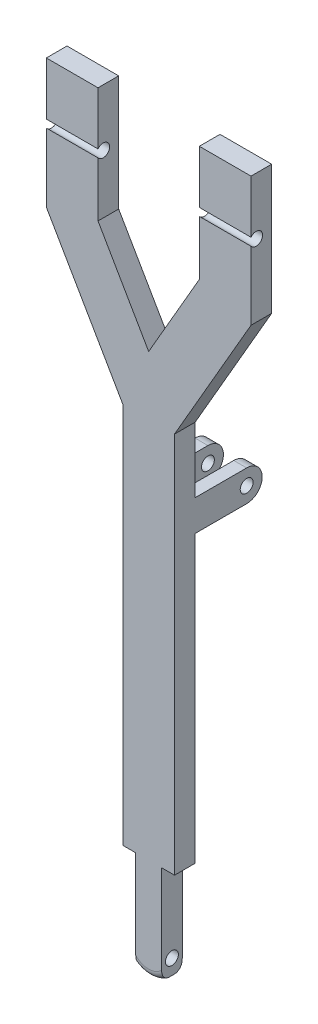
SolidWorks part; units mm, degrees
ref_plane "Plan de face" through (0, 0, 0) normal (0, 0, 1) x (1, 0, 0)
ref_plane "Plan de dessus" through (0, 0, 0) normal (0, 1, 0) x (1, 0, 0)
ref_plane "Plan de droite" through (0, 0, 0) normal (1, 0, 0) x (0, 0, -1)
sketch "Esquisse1" plane through (0, 0, 0) normal (0, 0, 1) x (1, 0, 0)
  line L0 (0, 0) -> (0, -900) construction
  line L1 (0, 0) -> (202.0726, 350) construction
  line L2 (0, 0) -> (-202.0726, 350) construction
  line L3 (0, -900) -> (0, 0) construction
  line L4 (-50, -900) -> (-50, 0)
  line L5 (50, -900) -> (50, 0)
  line L6 (0, 0) -> (202.0726, 350) construction
  line L8 (43.3013, -25) -> (198.0188, 242.9786)
  line L9 (-202.0726, 350) -> (0, 0) construction
  line L10 (-98.0188, 269.7735) -> (0, 100)
  line L11 (-198.0188, 242.9786) -> (-43.3013, -25)
  line L14 (-198.0188, 242.9786) -> (-198.0188, 492.9786)
  line L15 (-198.0188, 492.9786) -> (198.0188, 492.9786)
  line L16 (198.0188, 242.9786) -> (198.0188, 492.9786)
  line L20 (-98.0188, 342.9786) -> (-98.0188, 392.9786)
  line L22 (98.0188, 342.9786) -> (98.0188, 392.9786)
  line L24 (-98.0188, 342.9786) -> (-98.0188, 269.7735)
  line L26 (98.0188, 269.7735) -> (98.0188, 342.9786)
  line L27 (98.0188, 492.9786) -> (-98.0188, 492.9786)
  line L28 (-98.0188, 392.9786) -> (98.0188, 392.9786) construction
  line L29 (-98.0188, 342.9786) -> (98.0188, 342.9786) construction
  line L30 (-98.0188, 492.9786) -> (-98.0188, 392.9786)
  line L31 (98.0188, 392.9786) -> (98.0188, 492.9786)
  line L32 (0, 100) -> (98.0188, 269.7735)
  line L33 (-198.0188, 242.9786) -> (198.0188, 242.9786) construction
  arc A0 (-50, -900) -> (50, -900) centre (0, -900) ccw
  arc A1 (50, 0) -> (-50, 0) centre (0, 0) ccw
  arc A2 (-43.3013, 25) -> (-50, 0) centre (0, 0) ccw
  arc A5 (-43.3013, -25) -> (43.3013, -25) centre (0, 0) ccw
  arc A6 (-43.3013, -25) -> (43.3013, -25) centre (0, 0) ccw
  arc A7 (50, 0) -> (43.3013, 25) centre (0, 0) ccw
  point P3 (0, -450)
  point P10 (101.0363, 175)
  point P16 (-101.0363, 175)
  dimension "D1" = 900
  dimension "D2" = 60
  dimension "D3" = 30
  dimension "D4" = 350
  dimension "D5" = 100
  dimension "D6" = 250
  dimension "D7" = 100
  dimension "D10" = 100
extrude "Boss.-Extru.1" add sketch "Esquisse1" along normal blind 40 contours A5 L11 L4 A0 L5 L8 | L11 A5 L8 L5 A1 L4 | A1 L5 L8 L16 L15 L31 L22 L26 L32 L10 L24 L20 L30 L14 L11 L4
sketch "Esquisse2" plane through (0, 0, 0) normal (0, 0, -1) x (-1, 0, 0)
  line L0 (-50, -900) -> (-50, -13.3975) construction
  line L1 (-50, -752.6329) -> (50, -752.6329)
  line L2 (-50, -752.6329) -> (-50, -1037.9434)
  line L3 (-50, -1037.9434) -> (50, -1037.9434)
  line L4 (50, -752.6329) -> (50, -1037.9434)
  line L5 (-25, -752.6329) -> (-25, -1037.9434)
  line L6 (25, -752.6329) -> (25, -1037.9434)
  line M5 (-50, -13.3975) -> (-50, -900)
  arc M6 (-50, -900) -> (50, -900) centre (0, -900) ccw
  line M7 (50, -900) -> (50, -13.3975)
  dimension "D1" = 100
  dimension "D2" = 25
  dimension "D3" = 25
extrude "Enlèv. mat.-Extru.2" cut sketch "Esquisse2" against normal through all contours L6 L3 L4 M6 | L5 L2 L3 M6 | L5 L1 M5 M6 | L1 L6 M6 M7
sketch "Esquisse3" plane through (25, 0, 0) normal (1, 0, 0) x (0, 0, -1)
  line L0 (-20, -752.6329) -> (-20, -913.9756) construction
  line L1 (-40, -752.6329) -> (0, -752.6329) construction
  circle A0 centre (-20, -913.9756) radius 12.5
  dimension "D1" = 25
extrude "Enlèv. mat.-Extru.3" cut sketch "Esquisse3" against normal blind 50
fillet "Congé1" radius 15 2 edges at (0, -950, 40) (0, -950, 0)
sketch "Esquisse5" plane through (25, 0, 0) normal (1, 0, 0) x (0, 0, -1)
  point P0 (-20, -913.9756)
sketch "Esquisse4" plane through (0, 0, 0) normal (0, 0, -1) x (-1, 0, 0)
  line L0 (0, -172.1356) -> (0, -913.9756) construction
  line L2 (-25, -913.9756) -> (0, -913.9756) construction
  dimension "D1" = 741.84
sketch "Esquisse6" plane through (0, 0, 0) normal (1, 0, 0) x (0, 0, -1)
  line L0 (99.6584, -139.9093) -> (-10.6729, -139.9093)
  line L2 (-10.6729, -139.9093) -> (-10.6729, -199.9093)
  line L4 (-10.6729, -199.9093) -> (99.6584, -199.9093)
  circle A0 centre (99.6584, -169.9093) radius 12.5
  arc A1 (99.6584, -139.9093) -> (99.6584, -199.9093) centre (99.6584, -169.9093) cw
  circle A2 centre (99.6584, -169.9093) radius 12.5 construction
  dimension "D2" = 25
  dimension "D3" = 30
extrude "Boss.-Extru.2" add sketch "Esquisse6" along normal mid plane 100
extrude "Enlèv. mat.-Extru.4" cut sketch "Esquisse6" against normal mid plane 50
sketch "Esquisse7" plane through (198.0188, 0, 0) normal (1, 0, 0) x (0, 0, -1)
  line L1 (0, 242.9786) -> (0, 492.9786) construction
  line L2 (-40, 492.9786) -> (0, 492.9786) construction
  circle A0 centre (-30, 382.9786) radius 12.5
  dimension "D1" = 25
  dimension "D2" = 30
  dimension "D3" = 110
extrude "Enlèv. mat.-Extru.5" cut sketch "Esquisse7" against normal through all
